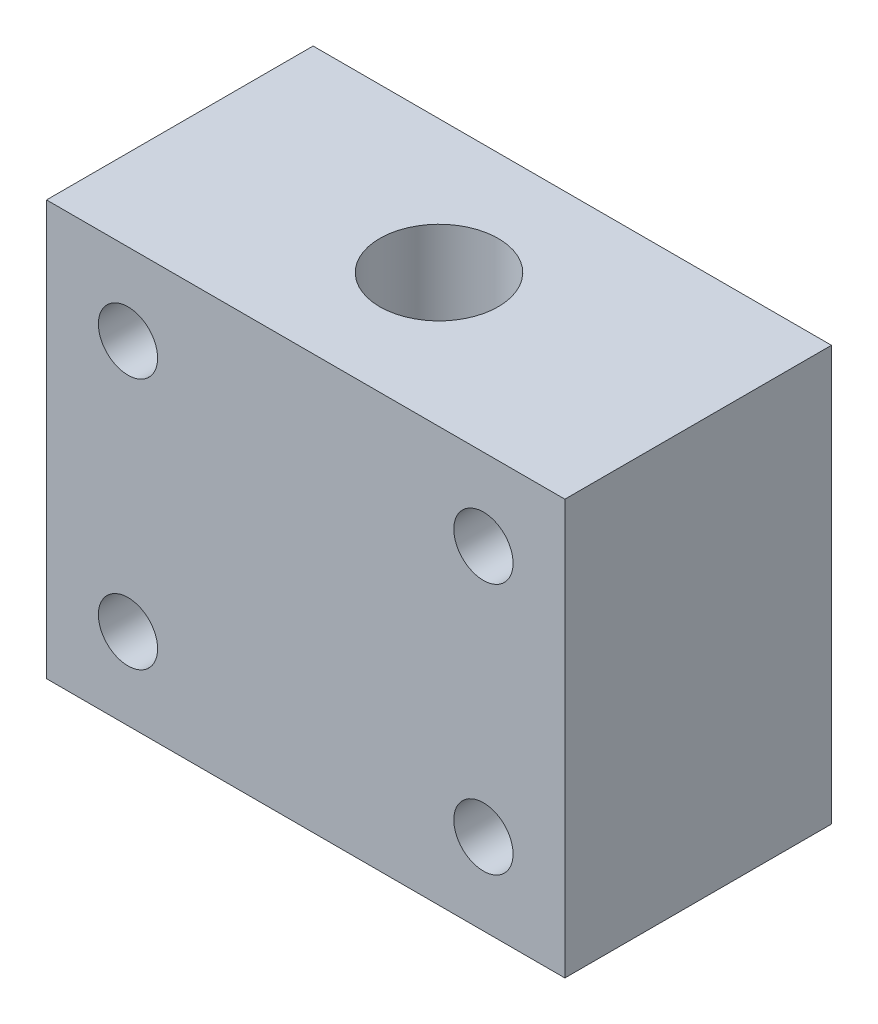
SolidWorks part; units mm, degrees
ref_plane "Front Plane" through (0, 0, 0) normal (0, 0, 1) x (1, 0, 0)
ref_plane "Top Plane" through (0, 0, 0) normal (0, 1, 0) x (1, 0, 0)
ref_plane "Right Plane" through (0, 0, 0) normal (1, 0, 0) x (0, 0, -1)
sketch "Sketch1" plane through (0, 0, 0) normal (0, 0, 1) x (1, 0, 0)
  line L0 (-13.5409, 19.779) -> (-13.5409, -8.221) construction
  line L1 (-31.0409, -8.221) -> (3.9591, -8.221)
  line L2 (-31.0409, -8.221) -> (-31.0409, 19.779)
  line L3 (-31.0409, 19.779) -> (3.9591, 19.779)
  line L4 (3.9591, -8.221) -> (3.9591, 19.779)
  line L5 (-31.0409, 5.779) -> (3.9591, 5.779) construction
  line L6 (-25.5409, 14.279) -> (-25.5409, -2.721) construction
  line L7 (-1.5409, 14.279) -> (-1.5409, -2.721) construction
  circle A0 centre (-25.5409, 14.279) radius 2
  circle A1 centre (-1.5409, 14.279) radius 2
  circle A2 centre (-25.5409, -2.721) radius 2
  circle A3 centre (-1.5409, -2.721) radius 2
  dimension "D3" = 4
  dimension "D4" = 4
  dimension "D5" = 4
  dimension "D6" = 4
  dimension "D1" = 28
  dimension "D2" = 35
  dimension "D7" = 24
  dimension "D8" = 24
  dimension "D9" = 17
  dimension "D10" = 8.5
  dimension "D11" = 12
extrude "Boss-Extrude1" add sketch "Sketch1" along normal blind 18
sketch "Sketch2" plane through (-4.2619, -8.221, 0) normal (0, 1, 0) x (0, 0, -1)
  line L0 (-9, 26.779) -> (-9, -8.221) construction
  line L3 (-18, 26.779) -> (0, 26.779) construction
  line L6 (-18, -8.221) -> (0, -8.221) construction
  line L7 (-18, 9.279) -> (0, 9.279) construction
  line L8 (-18, 26.779) -> (-18, -8.221) construction
  line L9 (0, 26.779) -> (0, -8.221) construction
  circle A0 centre (-9, 9.279) radius 4
  dimension "D1" = 8
extrude "Cut-Extrude1" cut sketch "Sketch2" along normal through all contours A0
